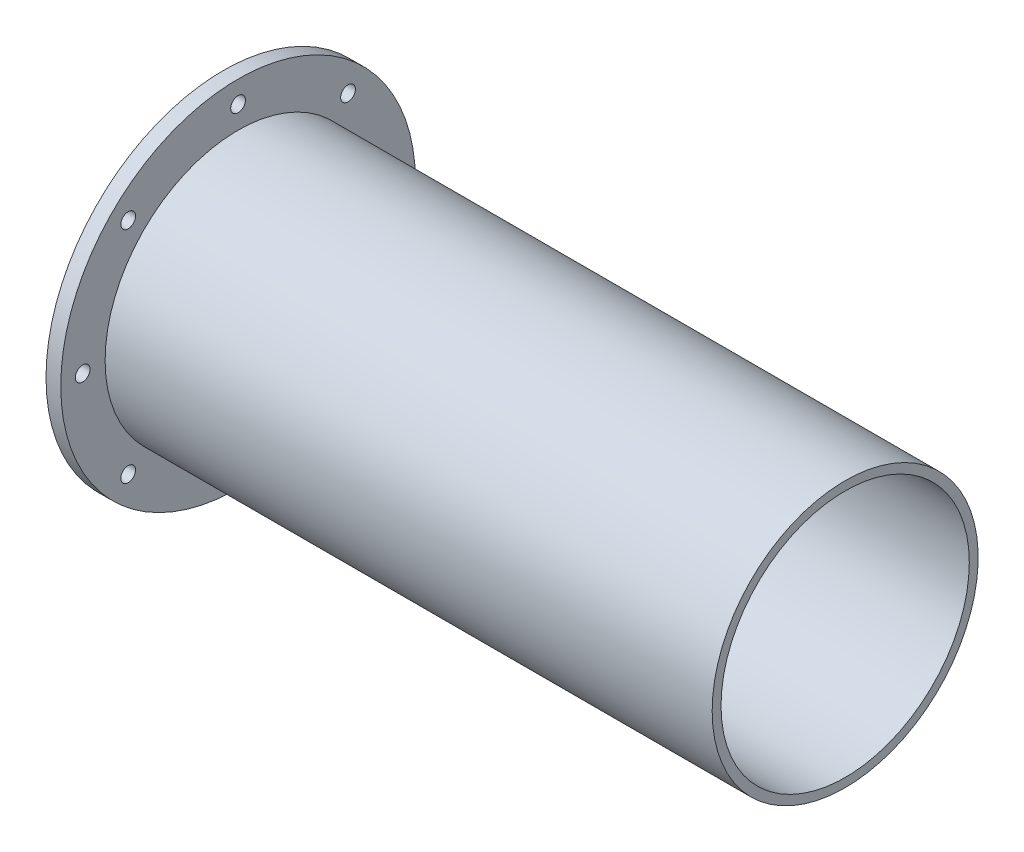
SolidWorks part; units mm, degrees
ref_plane "Front Plane" through (0, 0, 0) normal (0, 0, 1) x (1, 0, 0)
ref_plane "Top Plane" through (0, 0, 0) normal (0, 1, 0) x (1, 0, 0)
ref_plane "Right Plane" through (0, 0, 0) normal (1, 0, 0) x (0, 0, -1)
sketch "Sketch1" plane through (0, 0, 0) normal (0, 0, 1) x (1, 0, 0)
  line L1 (0, 76.2) -> (6.35, 76.2)
  line L2 (6.35, 76.2) -> (6.35, 57.15)
  line L3 (6.35, 57.15) -> (267.208, 57.15)
  line L4 (267.208, 57.15) -> (267.208, 53.34)
  line L5 (267.208, 53.34) -> (0, 53.34)
  line L8 (0, 0) -> (267.208, 0) construction
  line L9 (267.208, 0) -> (267.208, 53.34) construction
  line L10 (0, 76.2) -> (0, 53.34)
  dimension "D1" = 114.3
  dimension "D2" = 6.35
  dimension "D3" = 152.4
  dimension "D4" = 267.208
  dimension "D5" = 3.81
revolve "Revolve1" add sketch "Sketch1" angle 360 about L8
sketch "Sketch2" plane through (6.35, 0, 0) normal (1, 0, 0) x (0, 0, -1)
  line L0 (0, 0) -> (66.802, 0) construction
  circle A0 centre (66.802, 0) radius 3.175
  dimension "D2" = 6.35
  dimension "D1" = 66.802
extrude "Cut-Extrude1" cut sketch "Sketch2" against normal through all
pattern_circular "CirPattern1" count 8 over 360 about axis through (0, 0, 0) along (1, 0, 0) of "Cut-Extrude1"
equation "\"External Diameter\"=4.5"
equation "\"D1@Sketch1\"=\"External Diameter\""
equation "\"Screwing Space Section\"=0.25"
equation "\"D2@Sketch1\"=\"Screwing Space Section\""
equation "\"Comp\"=6"
equation "\"D3@Sketch1\"=\"Comp\""
equation "\"Shell Length\"=10.52"
equation "\"D4@Sketch1\"=\"Shell Length\""
equation "\"Wall Thickness\"=0.15"
equation "\"D5@Sketch1\"=\"Wall Thickness\""
equation "\"Screw Diameter\"=0.25"
equation "\"D2@Sketch2\"=\"Screw Diameter\""
equation "\"Screw Hole Diameter\"=2.625"
equation "\"Screw Hole Distance\"=2.63"
equation "\"D1@Sketch2\"=\"Screw Hole Distance\""
